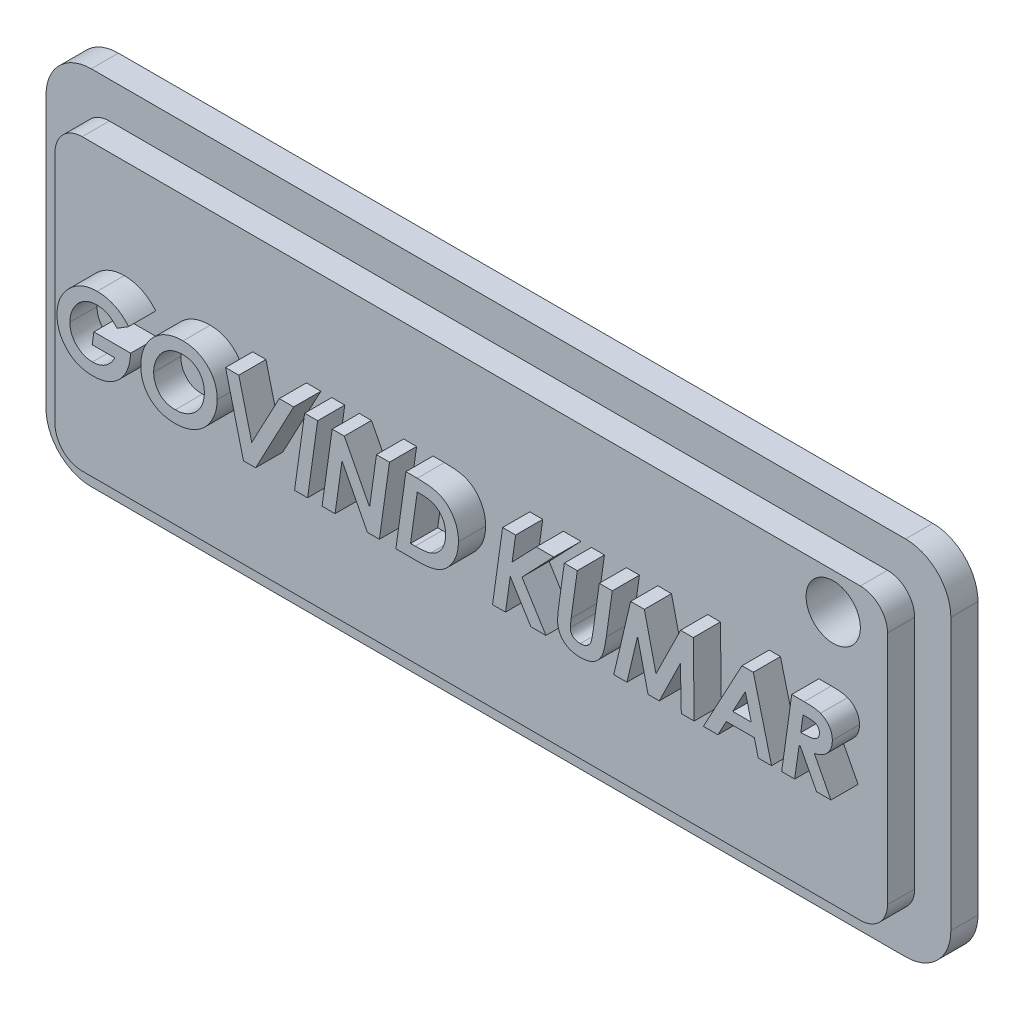
SolidWorks part; units mm, degrees
ref_plane "Front Plane" through (0, 0, 0) normal (0, 0, 1) x (1, 0, 0)
ref_plane "Top Plane" through (0, 0, 0) normal (0, 1, 0) x (1, 0, 0)
ref_plane "Right Plane" through (0, 0, 0) normal (1, 0, 0) x (0, 0, -1)
sketch "Sketch1" plane through (0, 0, 0) normal (0, 0, 1) x (1, 0, 0)
  line L1 (-22.5, -10) -> (22.5, -10)
  line L2 (-25, -7.5) -> (-25, 7.5)
  line L3 (-22.5, 10) -> (22.5, 10)
  line L4 (25, -7.5) -> (25, 7.5)
  line L5 (-25, -10) -> (25, 10) construction
  line L6 (-25, 10) -> (25, -10) construction
  arc A0 (-22.5, -10) -> (-25, -7.5) centre (-22.5, -7.5) cw
  arc A1 (25, -7.5) -> (22.5, -10) centre (22.5, -7.5) cw
  arc A2 (25, 7.5) -> (22.5, 10) centre (22.5, 7.5) ccw
  arc A3 (-22.5, 10) -> (-25, 7.5) centre (-22.5, 7.5) ccw
  point P0 (0, 0)
  dimension "D3" = 2.5
  dimension "D1" = 20
  dimension "D2" = 50
extrude "Boss-Extrude1" add sketch "Sketch1" along normal blind 1.5
sketch "Sketch2" plane through (0, 0, 1.5) normal (0, 0, 1) x (1, 0, 0)
  line L0 (-25, 7.5) -> (-25, -7.5) construction
  line L1 (-21.5, -8) -> (21.5, -8)
  line L2 (-23, -6.5) -> (-23, 6.5)
  line L3 (-21.5, 8) -> (21.5, 8)
  line L4 (23, -6.5) -> (23, 6.5)
  line L5 (-23, -8) -> (23, 8) construction
  line L6 (-23, 8) -> (23, -8) construction
  line L7 (22.5, 10) -> (-22.5, 10) construction
  arc A0 (-21.5, -8) -> (-23, -6.5) centre (-21.5, -6.5) cw
  arc A1 (23, -6.5) -> (21.5, -8) centre (21.5, -6.5) cw
  arc A2 (23, 6.5) -> (21.5, 8) centre (21.5, 6.5) ccw
  arc A3 (-21.5, 8) -> (-23, 6.5) centre (-21.5, 6.5) ccw
  point P0 (0, 0)
  dimension "D3" = 1.5
  dimension "D1" = 2
  dimension "D2" = 2
extrude "Boss-Extrude2" add sketch "Sketch2" along normal blind 1.5
sketch "Sketch3" plane through (0, 0, 3) normal (0, 0, 1) x (1, 0, 0)
  text T0 "GOVIND KUMAR" font "Century Gothic" height in points 15
extrude "Boss-Extrude3" add sketch "Sketch3" along normal blind 1.5
sketch "Sketch4" plane through (0, 0, 3) normal (0, 0, 1) x (1, 0, 0)
  line L0 (23, -6.5) -> (23, 6.5) construction
  line L1 (21.5, 8) -> (-21.5, 8) construction
  circle A0 centre (20, 6) radius 1.5
  dimension "D1" = 3
  dimension "D2" = 2
extrude "Cut-Extrude1" cut sketch "Sketch4" against normal blind 3
